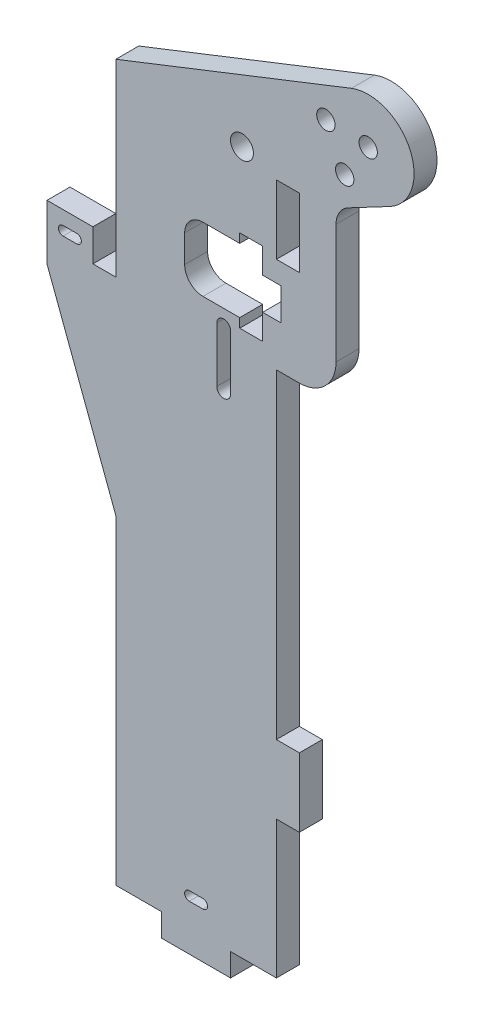
SolidWorks part; units mm, degrees
ref_plane "Front Plane" through (0, 0, 0) normal (0, 0, 1) x (1, 0, 0)
ref_plane "Top Plane" through (0, 0, 0) normal (0, 1, 0) x (1, 0, 0)
ref_plane "Right Plane" through (0, 0, 0) normal (1, 0, 0) x (0, 0, -1)
sketch "Sketch2" plane through (0, 0, 0) normal (0, 0, 1) x (1, 0, 0)
  line L7 (5, 114.7865) -> (0, 114.7865) construction
  line L9 (20, 166.7865) -> (10.7809, 167.3702) construction
  line L10 (-80, 155.908) -> (-95, 155.908) construction
  line L16 (16.3411, 176.0931) -> (-35, 155.908)
  line L17 (24.6666, 157.9421) -> (13, 151.7865)
  line L18 (5, 114.7865) -> (0, 114.7865)
  line L19 (-35, 155.908) -> (-35, 0)
  line L21 (0, 114.7865) -> (0, 45)
  line L22 (0, 0) -> (-10, 0)
  line L23 (13, 151.7865) -> (13, 122.7865)
  line L24 (-10, 0) -> (-10, -5)
  line L25 (-10, -5) -> (-25, -5)
  line L26 (-25, -5) -> (-25, 0)
  line L27 (-25, 0) -> (-35, 0)
  line L28 (0, 30) -> (5, 30)
  line L29 (5, 30) -> (5, 45)
  line L30 (5, 45) -> (0, 45)
  line L31 (0, 30) -> (0, 0)
  line L32 (10.7809, 167.3702) -> (14.885, 159.0943) construction
  line L33 (-35, 155.908) -> (-50, 155.908) construction
  line L34 (14.885, 159.0943) -> (20, 166.7865) construction
  line L35 (-7.5, 153.1488) -> (20, 166.7865) construction
  arc A1 (16.3411, 176.0931) -> (24.6666, 157.9421) centre (20, 166.7865) cw
  circle A2 centre (20, 166.7865) radius 2
  arc A3 (5, 114.7865) -> (13, 122.7865) centre (5, 122.7865) ccw
  circle A4 centre (10.7809, 167.3702) radius 2
  circle A5 centre (14.885, 159.0943) radius 2
  point P31 (12.8329, 163.2322)
  dimension "D2" = 10
  dimension "D8" = 4
  dimension "D1" = 35
  dimension "D3" = 5
  dimension "D4" = 15
  dimension "D5" = 8
  dimension "D6" = 37
  dimension "D7" = 15
  dimension "D9" = 5
  dimension "D10" = 15
  dimension "D11" = 15
  dimension "D12" = 5
  dimension "D13" = 30
  dimension "D14" = 8
extrude "Boss-Extrude1" add sketch "Sketch2" along normal blind 5
sketch "Sketch3" plane through (0, 0, 5) normal (0, 0, 1) x (1, 0, 0)
  line L0 (-3, 136.6475) -> (-3, 131.1475)
  line L1 (-3, 136.6475) -> (-8, 136.6475)
  line L2 (-3, 118.6475) -> (-8, 118.6475)
  line L3 (-8, 136.6475) -> (-8, 134.6475)
  line L4 (-8, 134.6475) -> (-20, 134.6475)
  line L5 (-20, 134.6475) -> (-20, 120.6475)
  line L6 (-20, 120.6475) -> (-8, 120.6475)
  line L7 (1, 127.6475) -> (-20, 127.6475) construction
  line L8 (-8, 120.6475) -> (-8, 118.6475)
  line L9 (-11.5, 134.6475) -> (-11.5, 120.6475) construction
  line L10 (-7.5, 153.1488) -> (-7.5, 127.6475) construction
  line L11 (-3, 124.1475) -> (1, 124.1475)
  line L12 (1, 124.1475) -> (1, 131.1475)
  line L13 (1, 131.1475) -> (-3, 131.1475)
  line L14 (-3, 124.1475) -> (-3, 118.6475)
  line L17 (-3, 118.6475) -> (-8, 118.6475) construction
  circle A0 centre (-7.5, 153.1488) radius 2.5
  ellipse E1 centre (-7, 7.7758) end of major axis (-11.5, 7.7758) minor radius 4.127 construction
  dimension "D8" = 5
  dimension "D1" = 5
  dimension "D2" = 18
  dimension "D3" = 12
  dimension "D4" = 14
  dimension "D5" = 7
  dimension "D6" = 4
  dimension "D7" = 0.5
  dimension "D9" = 3.5
  dimension "D10" = 149.5
extrude "Cut-Extrude1" cut sketch "Sketch3" against normal through all
sketch "Sketch4" plane through (0, 0, 0) normal (0, 0, -1) x (-1, 0, 0)
  line L0 (40, 114.7865) -> (35, 114.7865)
  line L1 (35, 155.908) -> (35, 0) construction
  line L2 (35, 0) -> (25, 0) construction
  line L5 (40, 114.7865) -> (40, 121.7865)
  line L6 (40, 121.7865) -> (50, 121.7865)
  line L7 (50, 121.7865) -> (50, 109.7865)
  line L9 (35, 155.908) -> (35, 0) construction
  line L10 (35, 69.7865) -> (50, 109.7865)
  line L18 (35, 114.7865) -> (35, 69.7865)
  dimension "D1" = 10
  dimension "D2" = 5
  dimension "D3" = 5
  dimension "D4" = 40
  dimension "D5" = 114.7865
  dimension "D6" = 7
extrude "Boss-Extrude2" add sketch "Sketch4" against normal up to surface (5 mm away) up to face at (-6.8333, 127.6475, 5)
fillet "Fillet1" radius 5 1 edges at (13, 151.7865, 2.5)
sketch "Sketch5" plane through (0, 0, 5) normal (0, 0, 1) x (1, 0, 0)
  line L0 (-11.5, 117.1475) -> (-11.5, 105.1475) construction
  line L1 (-10, 117.1475) -> (-10, 105.1475)
  line L2 (-13, 117.1475) -> (-13, 105.1475)
  line L3 (-11.5, 123.6475) -> (-11.5, 131.6475) construction
  line L4 (-11.5, 123.6475) -> (-11.5, 131.6475) construction
  line L5 (-45, 121.7865) -> (-45, 118.7865) construction
  line L6 (-50, 121.7865) -> (-40, 121.7865) construction
  line L7 (-11.5, 118.6475) -> (-15.0807, 118.6475) construction
  line L8 (-20, 120.6475) -> (-8, 120.6475) construction
  line L9 (-43.5, 117.7865) -> (-46.5, 117.7865) construction
  line L10 (-43.5, 116.7865) -> (-46.5, 116.7865)
  line L11 (-43.5, 118.7865) -> (-46.5, 118.7865)
  line L14 (-19, 6) -> (-16, 6) construction
  line L15 (-19, 7) -> (-16, 7)
  line L16 (-19, 5) -> (-16, 5)
  line L17 (-17.5, 6) -> (-17.5, 0) construction
  line L18 (-10, 0) -> (-25, 0) construction
  line L19 (-35, 0) -> (-25, 0) construction
  arc A0 (-10, 117.1475) -> (-13, 117.1475) centre (-11.5, 117.1475) ccw
  arc A1 (-13, 105.1475) -> (-10, 105.1475) centre (-11.5, 105.1475) ccw
  arc A2 (-43.5, 116.7865) -> (-43.5, 118.7865) centre (-43.5, 117.7865) ccw
  arc A3 (-46.5, 118.7865) -> (-46.5, 116.7865) centre (-46.5, 117.7865) ccw
  arc A4 (-19, 7) -> (-19, 5) centre (-19, 6) ccw
  arc A5 (-16, 5) -> (-16, 7) centre (-16, 6) ccw
  point P2 (-11.5, 111.1475)
  point P15 (-45, 117.7865)
  point P24 (-17.5, 6)
  dimension "D1" = 3
  dimension "D2" = 12
  dimension "D3" = 2
  dimension "D4" = 3
  dimension "D5" = 2
  dimension "D6" = 3
  dimension "D7" = 5
extrude "Cut-Extrude2" cut sketch "Sketch5" against normal through all
sketch "Sketch6" plane through (0, 0, 0) normal (0, 0, -1) x (-1, 0, 0)
  line L4 (0, 135.6488) -> (0, 150.6488)
  line L5 (0, 150.6488) -> (-5, 150.6488)
  line L6 (-5, 150.6488) -> (-5, 135.6488)
  line L7 (-5, 135.6488) -> (0, 135.6488)
  line L8 (0, 135.6488) -> (0, 150.6488)
  line L9 (0, 150.6488) -> (-5, 150.6488)
  line L10 (-5, 150.6488) -> (-5, 135.6488)
  line L11 (-5, 135.6488) -> (0, 135.6488)
  dimension "D1" = 0
extrude "Cut-Extrude3" cut sketch "Sketch6" against normal through all
fillet "Fillet2" radius 4 2 edges at (-20, 134.6475, 2.5) (-20, 120.6475, 2.5)
equation "\"D3@Sketch2\"=\"thickness_plates@ankare 3 linor.Assembly\""
